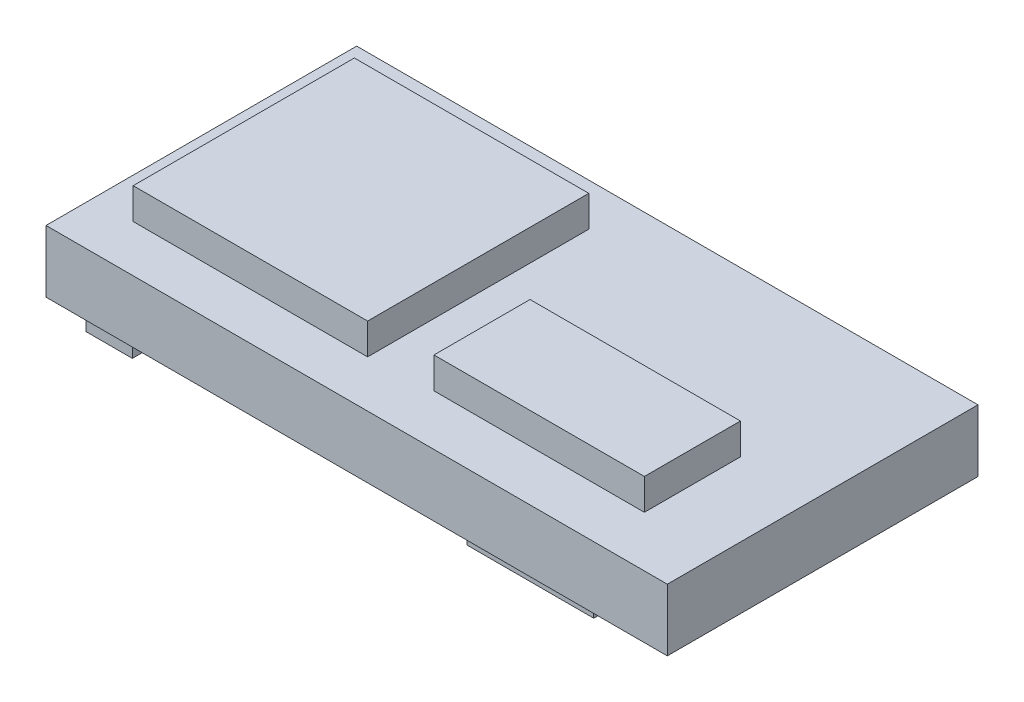
SolidWorks part; units mm, degrees
ref_plane "Front Plane" through (0, 0, 0) normal (0, 0, 1) x (1, 0, 0)
ref_plane "Top Plane" through (0, 0, 0) normal (0, 1, 0) x (1, 0, 0)
ref_plane "Right Plane" through (0, 0, 0) normal (1, 0, 0) x (0, 0, -1)
sketch "Sketch1" plane through (0, 0, 0) normal (0, 1, 0) x (1, 0, 0)
  line L1 (12.7, -6.35) -> (-12.7, -6.35)
  line L2 (12.7, -6.35) -> (12.7, 6.35)
  line L3 (12.7, 6.35) -> (-12.7, 6.35)
  line L4 (-12.7, -6.35) -> (-12.7, 6.35)
  line L5 (12.7, -6.35) -> (-12.7, 6.35) construction
  line L6 (12.7, 6.35) -> (-12.7, -6.35) construction
  point P0 (0, 0)
  dimension "D1" = 12.7
  dimension "D2" = 25.4
extrude "Boss-Extrude1" add sketch "Sketch1" along normal blind 2.54
sketch "Sketch2" plane through (0, 2.54, 0) normal (0, 1, 0) x (1, 0, 0)
  line L1 (-11.0562, 4.6111) -> (-1.4724, 4.6111)
  line L2 (-11.0562, 4.6111) -> (-11.0562, -4.4302)
  line L3 (-11.0562, -4.4302) -> (-1.4724, -4.4302)
  line L4 (-1.4724, 4.6111) -> (-1.4724, -4.4302)
  line L5 (1.085, -0.3487) -> (9.6871, -0.3487)
  line L6 (1.085, -0.3487) -> (1.085, -4.2752)
  line L7 (1.085, -4.2752) -> (9.6871, -4.2752)
  line L8 (9.6871, -0.3487) -> (9.6871, -4.2752)
  point P8 (-3.7973, 2.6736)
  point P9 (4.3657, -4.4302)
  point P10 (1.085, -0.3487)
  point P11 (9.6871, -4.2752)
  point P12 (-1.4724, -4.4302)
extrude "Boss-Extrude2" add sketch "Sketch2" along normal blind 1.27
sketch "Sketch3" plane through (0, 0, 0) normal (0, -1, 0) x (1, 0, 0)
  line L1 (1.5899, -2.2372) -> (-3.917, -2.2372)
  line L2 (1.5899, -2.2372) -> (1.5899, 3.6568)
  line L3 (1.5899, 3.6568) -> (-3.917, 3.6568)
  line L4 (-3.917, -2.2372) -> (-3.917, 3.6568)
  line L5 (-10.0392, -5.2141) -> (-11.9296, -5.2141)
  line L6 (-10.0392, -5.2141) -> (-10.0392, -2.2372)
  line L7 (-10.0392, -2.2372) -> (-11.9296, -2.2372)
  line L8 (-11.9296, -5.2141) -> (-11.9296, -2.2372)
  line L9 (-10.0392, -1.0942) -> (-11.9296, -1.0942)
  line L10 (-10.0392, -1.0942) -> (-10.0392, 1.8324)
  line L11 (-10.0392, 1.8324) -> (-11.9296, 1.8324)
  line L12 (-11.9296, -1.0942) -> (-11.9296, 1.8324)
  line L13 (-10.0392, 2.8689) -> (-11.9296, 2.8689)
  line L14 (-10.0392, 2.8689) -> (-10.0392, 5.4817)
  line L15 (-10.0392, 5.4817) -> (-11.9296, 5.4817)
  line L16 (-11.9296, 2.8689) -> (-11.9296, 5.4817)
  line L17 (8.5914, 1.3851) -> (3.4183, 1.3851)
  line L18 (8.5914, 1.3851) -> (8.5914, 5.2507)
  line L19 (8.5914, 5.2507) -> (3.4183, 5.2507)
  line L20 (3.4183, 1.3851) -> (3.4183, 5.2507)
extrude "Boss-Extrude3" add sketch "Sketch3" along normal blind 1.27
